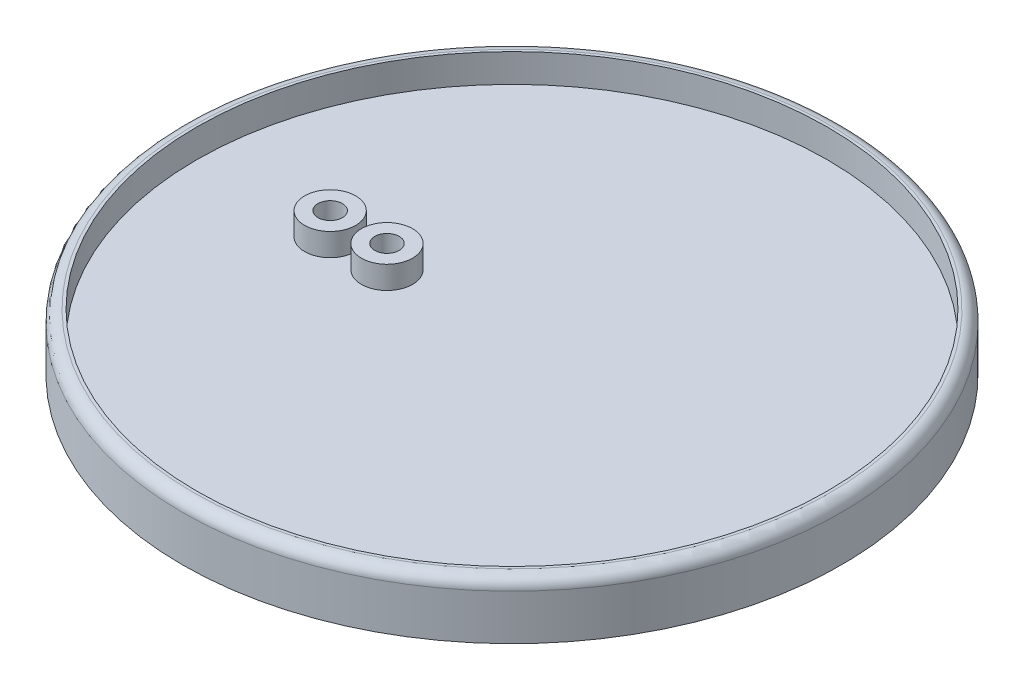
SolidWorks part; units mm, degrees
ref_plane "前视基准面" through (0, 0, 0) normal (0, 0, 1) x (1, 0, 0)
ref_plane "上视基准面" through (0, 0, 0) normal (0, 1, 0) x (1, 0, 0)
ref_plane "右视基准面" through (0, 0, 0) normal (1, 0, 0) x (0, 0, -1)
other "Configuration Table"
sketch "草图1" plane through (0, 0, 0) normal (0, 1, 0) x (1, 0, 0)
  circle A0 centre (-22, 0) radius 4.5
extrude "Moving_post_A" add sketch "草图1" along normal blind 9
sketch "草图2" plane through (0, 0, 0) normal (0, 1, 0) x (1, 0, 0)
  circle A0 centre (0, 0) radius 58
extrude "Cup_plate_D116_T5" add sketch "草图2" along normal blind 5
sketch "草图3" plane through (0, 0, 0) normal (0, 1, 0) x (1, 0, 0)
  circle A0 centre (-32, 0) radius 4.5
extrude "Moving_post_B" add sketch "草图3" along normal blind 9
sketch "草图4" plane through (0, 0, 0) normal (0, 1, 0) x (1, 0, 0)
  circle A0 centre (0, 0) radius 58
  circle A1 centre (0, 0) radius 55.5
extrude "Drip_skirt_OD116_ID111_H10" add sketch "草图4" along normal blind 10
sketch "草图5" plane through (0, 0, 0) normal (0, 1, 0) x (1, 0, 0)
  circle A0 centre (-22, 0) radius 2.15
  circle A1 centre (-32, 0) radius 2.15
extrude "M4_moving_mount_clearance" cut sketch "草图5" along normal blind 9
sketch "草图6" plane through (0, 0, 0) normal (0, 1, 0) x (1, 0, 0)
  circle A0 centre (-22, 0) radius 4.5
  circle A1 centre (-32, 0) radius 4.5
extrude "M4_moving_head_recess_D8p2_T2p7" cut sketch "草图6" along normal blind 2.7
fillet "Cup_top_outer_round_R2" radius 2 1 edges at (0, 10, 58)
